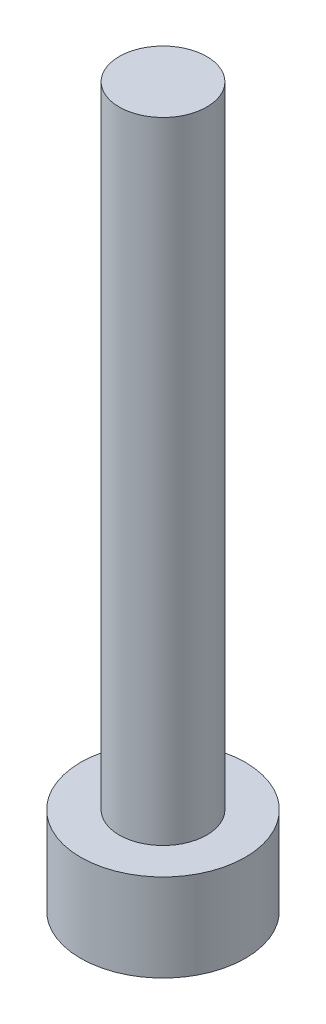
SolidWorks part; units mm, degrees
material "AISI 304"
ref_plane "Front" through (0, 0, 0) normal (0, 0, 1) x (1, 0, 0)
ref_plane "Top" through (0, 0, 0) normal (0, 1, 0) x (1, 0, 0)
ref_plane "Right" through (0, 0, 0) normal (1, 0, 0) x (0, 0, -1)
sketch "草图1" plane through (0, 0, 0) normal (0, 1, 0) x (1, 0, 0)
  circle A0 centre (0, 0) radius 2.35
  dimension "D1" = 4.7
extrude "螺帽" add sketch "草图1" along normal blind 2.5
sketch "草图2" plane through (0, 2.5, 0) normal (0, 1, 0) x (1, 0, 0)
  circle A0 centre (0, 0) radius 1.25
  dimension "D1" = 2.5
extrude "螺纹" add sketch "草图2" along normal blind 18
